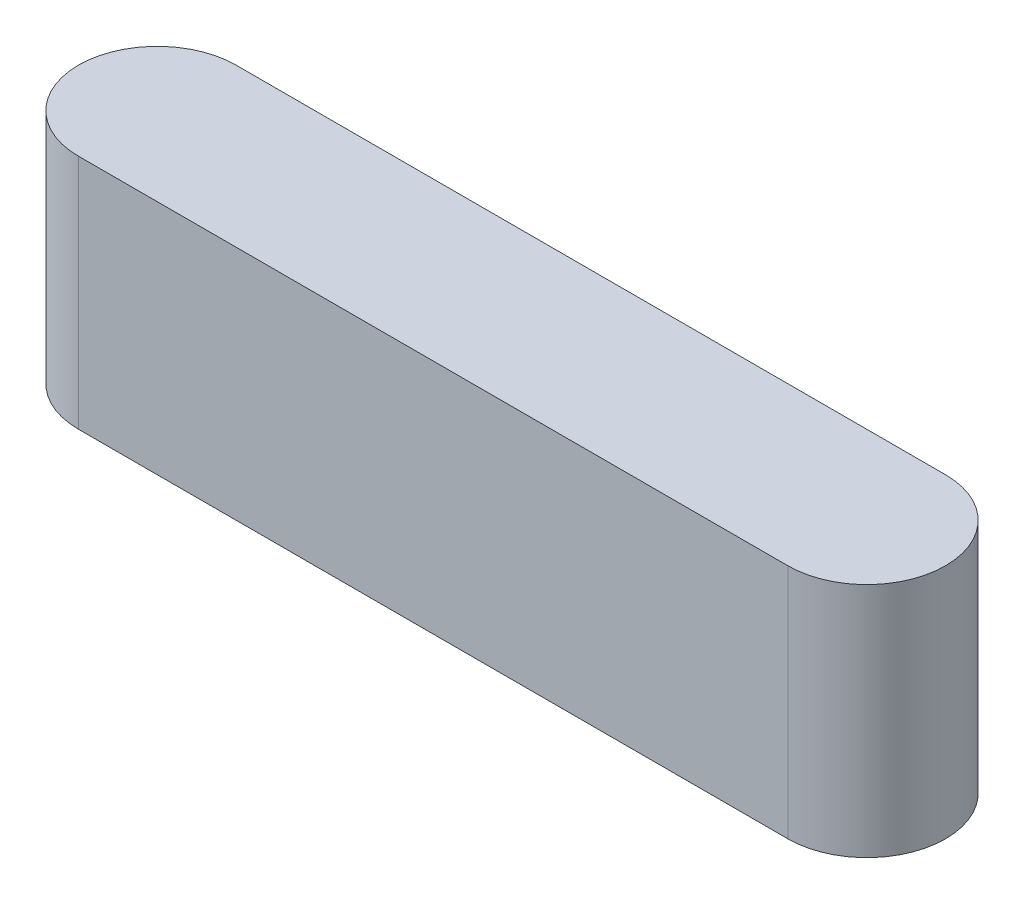
SolidWorks part; units mm, degrees
ref_plane "Front Plane" through (0, 0, 0) normal (0, 0, 1) x (1, 0, 0)
ref_plane "Top Plane" through (0, 0, 0) normal (0, 1, 0) x (1, 0, 0)
ref_plane "Right Plane" through (0, 0, 0) normal (1, 0, 0) x (0, 0, -1)
sketch "Sketch1" plane through (0, 0, 0) normal (0, 1, 0) x (1, 0, 0)
  line L1 (-22.5, -5) -> (22.5, -5)
  line L3 (-22.5, 5) -> (22.5, 5)
  line L5 (-22.5, -5) -> (22.5, 5) construction
  line L6 (-22.5, 5) -> (22.5, -5) construction
  arc A0 (-22.5, 5) -> (-22.5, -5) centre (-22.5, 0) ccw
  arc A1 (22.5, -5) -> (22.5, 5) centre (22.5, 0) ccw
  point P0 (0, 0)
  dimension "D1" = 45
  dimension "D2" = 10
extrude "Boss-Extrude1" add sketch "Sketch1" along normal mid plane 15
